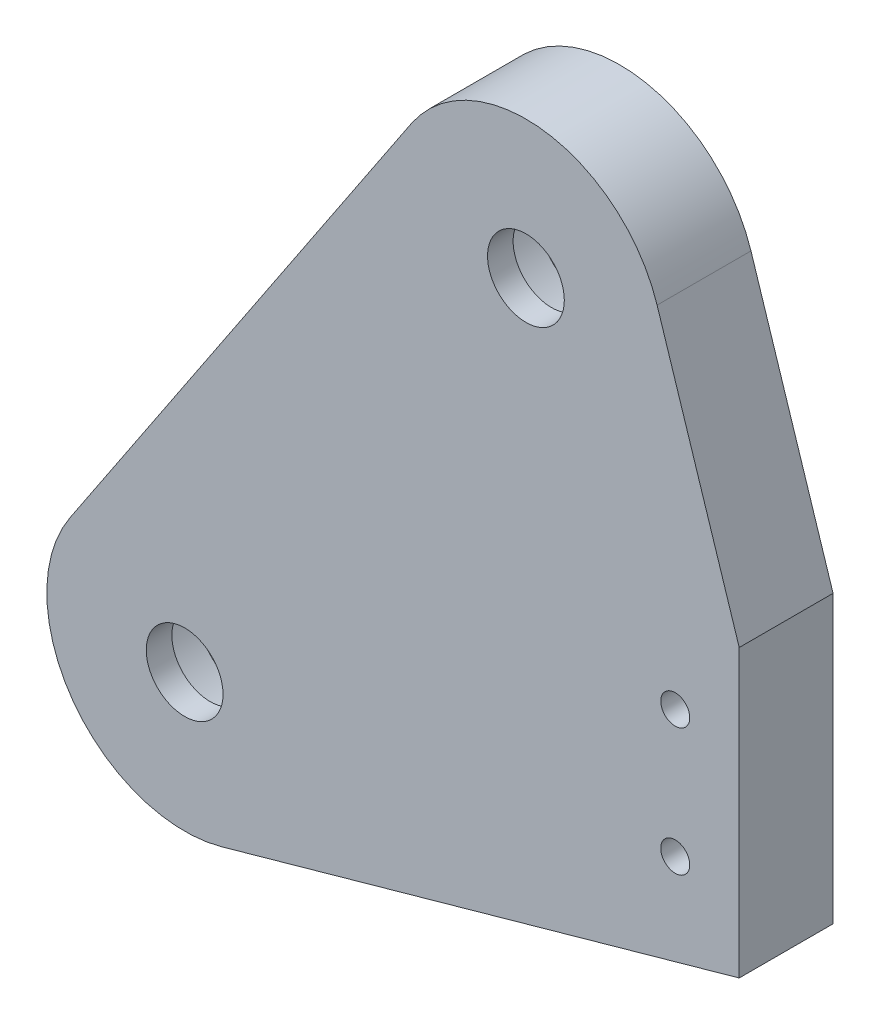
SolidWorks part; units mm, degrees
ref_plane "Front Plane" through (0, 0, 0) normal (0, 0, 1) x (1, 0, 0)
ref_plane "Top Plane" through (0, 0, 0) normal (0, 1, 0) x (1, 0, 0)
ref_plane "Right Plane" through (0, 0, 0) normal (1, 0, 0) x (0, 0, -1)
other "Configuration Table"
sketch "Sketch1" plane through (0, 0, 0) normal (0, 0, 1) x (1, 0, 0)
  line L0 (0, 0) -> (0, -30) construction
  line L1 (0, -30) -> (65, -30) construction
  line L2 (65, 1.4541) -> (65, 35)
  line L3 (-4.3605, 15.5502) -> (65, 35) construction
  line L4 (4.3605, -15.5502) -> (65, 1.4541)
  line L5 (57.5, 30) -> (57.5, 5) construction
  line L6 (65, 5) -> (65, 30) construction
  line L7 (65, -30) -> (65, 1.4541) construction
  line L8 (65, 30) -> (50, 30) construction
  line L9 (50, 30) -> (50, 5) construction
  line L10 (50, 5) -> (65, 5) construction
  line L11 (55.3752, 64.9423) -> (65, 35)
  line L12 (26.5624, 68.9584) -> (-13.4376, 8.9584)
  circle A0 centre (0, 0) radius 11.15
  arc A1 (-13.4376, 8.9584) -> (4.3605, -15.5502) centre (0, 0) ccw
  arc A2 (4.3605, -15.5502) -> (-4.3605, 15.5502) centre (0, 0) ccw construction
  circle A3 centre (0, 0) radius 16.15 construction
  circle A4 centre (57.5, 24.9667) radius 1.7
  circle A5 centre (57.5, 10.0333) radius 1.7
  circle A6 centre (40, 60) radius 11.15
  arc A7 (55.3752, 64.9423) -> (26.5624, 68.9584) centre (40, 60) ccw
  arc A8 (-4.3605, 15.5502) -> (-13.4376, 8.9584) centre (0, 0) ccw construction
  arc A9 (26.5624, 68.9584) -> (55.3752, 64.9423) centre (40, 60) ccw construction
  circle A10 centre (40, 60) radius 16.15 construction
  point P6 (65, 30)
  point P26 (40, 60)
  dimension "D1" = 22.3
  dimension "D9" = 3.4
  dimension "D14" = 22.3
  dimension "D15" = 5
  dimension "D2" = 30
  dimension "D3" = 5
  dimension "D4" = 65
  dimension "D5" = 65
  dimension "D6" = 5
  dimension "D7" = 3.3333
  dimension "D8" = 3.3333
  dimension "D10" = 25
  dimension "D11" = 15
  dimension "D12" = 40
  dimension "D13" = 30
  dimension "D16" = 72.0359
extrude "Boss-Extrude1" add sketch "Sketch1" against normal blind 8
sketch "Sketch2" plane through (0, 0, 0) normal (0, 0, 1) x (1, 0, 0)
  line L3 (65, 35) -> (55.3752, 64.9423)
  line L4 (4.3605, -15.5502) -> (65, 1.4541)
  line L5 (65, 1.4541) -> (65, 35)
  line L7 (4.3605, -15.5502) -> (65, 1.4541)
  line L8 (65, 1.4541) -> (65, 35)
  line L10 (65, 35) -> (55.3752, 64.9423)
  line L11 (26.5624, 68.9584) -> (-13.4376, 8.9584)
  line L12 (26.5624, 68.9584) -> (-13.4376, 8.9584)
  circle A0 centre (0, 0) radius 4.5
  arc A1 (-13.4376, 8.9584) -> (4.3605, -15.5502) centre (0, 0) ccw
  arc A2 (-13.4376, 8.9584) -> (4.3605, -15.5502) centre (0, 0) ccw
  circle A3 centre (57.5, 24.9667) radius 1.7 construction
  circle A4 centre (57.5, 10.0333) radius 1.7 construction
  circle A5 centre (57.5, 24.9667) radius 1.7
  circle A6 centre (57.5, 10.0333) radius 1.7
  circle A7 centre (40, 60) radius 4.5
  arc A9 (55.3752, 64.9423) -> (26.5624, 68.9584) centre (40, 60) ccw
  arc A10 (55.3752, 64.9423) -> (26.5624, 68.9584) centre (40, 60) ccw
  dimension "D2" = 9
  dimension "D1" = 0
extrude "Boss-Extrude2" add sketch "Sketch2" along normal blind 3
